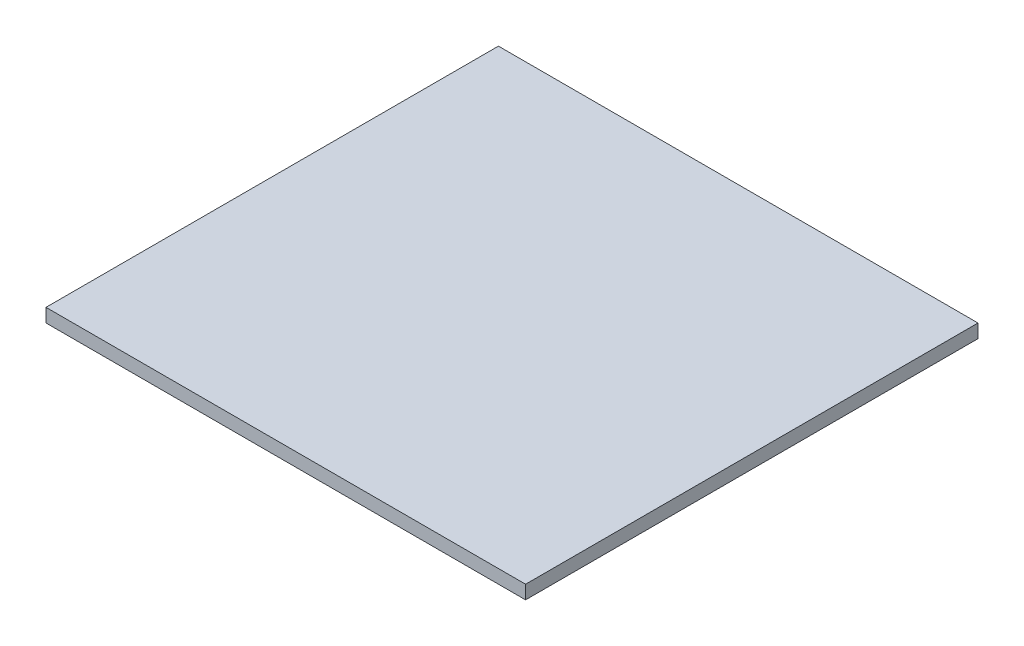
SolidWorks part; units mm, degrees
material "Perspex (TM) GS Acrylic Cast Sheet"
ref_plane "Front Plane" through (0, 0, 0) normal (0, 0, 1) x (1, 0, 0)
ref_plane "Top Plane" through (0, 0, 0) normal (0, 1, 0) x (1, 0, 0)
ref_plane "Right Plane" through (0, 0, 0) normal (1, 0, 0) x (0, 0, -1)
sketch "Sketch1" plane through (0, 0, 0) normal (0, 1, 0) x (1, 0, 0)
  line L1 (-79.5, -75) -> (79.5, -75)
  line L2 (-79.5, -75) -> (-79.5, 75)
  line L3 (-79.5, 75) -> (79.5, 75)
  line L4 (79.5, -75) -> (79.5, 75)
  line L5 (-79.5, -75) -> (79.5, 75) construction
  line L6 (-79.5, 75) -> (79.5, -75) construction
  point P0 (0, 0)
  point P5 (0, 0)
  dimension "D1" = 150
  dimension "D2" = 159
extrude "Boss-Extrude1" add sketch "Sketch1" along normal blind 4.5
